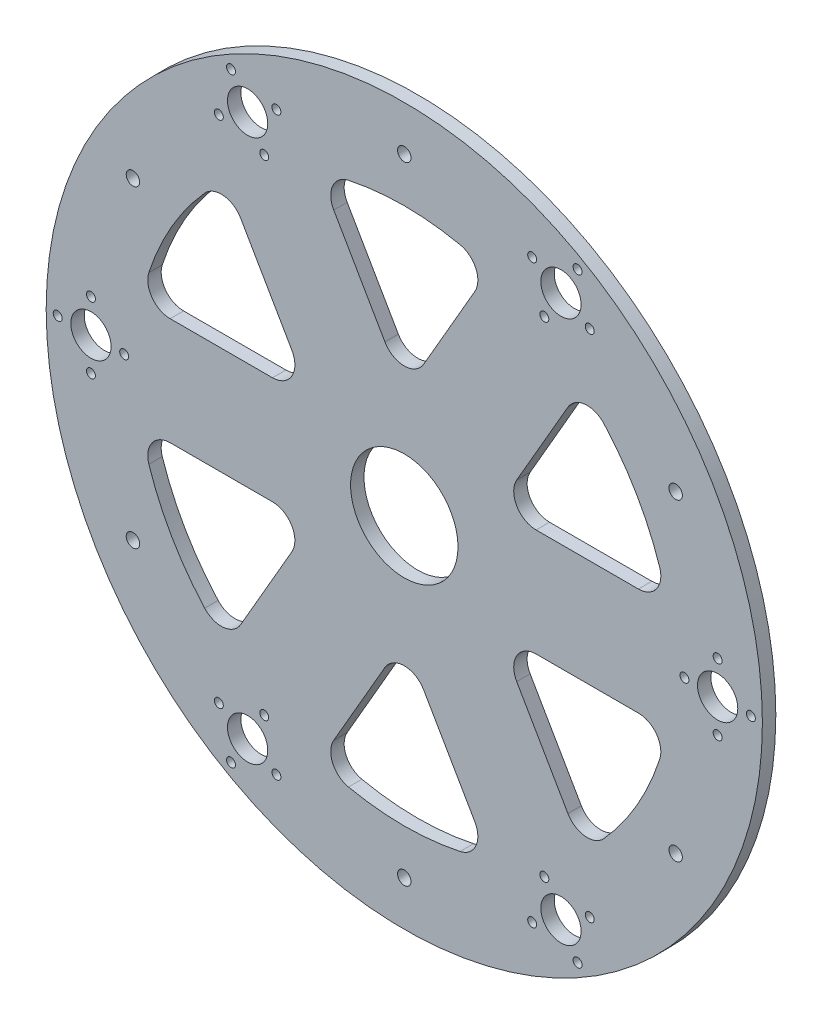
SolidWorks part; units mm, degrees
ref_plane "Front Plane" through (0, 0, 0) normal (0, 0, 1) x (1, 0, 0)
ref_plane "Top Plane" through (0, 0, 0) normal (0, 1, 0) x (1, 0, 0)
ref_plane "Right Plane" through (0, 0, 0) normal (1, 0, 0) x (0, 0, -1)
sketch "Sketch1" plane through (0, 0, 0) normal (0, 0, 1) x (1, 0, 0)
  line L0 (-561.3531, -948.2921) -> (24438.6469, 42352.9781) construction
  line L1 (-540.4731, -960.1269) -> (24459.5269, 42341.1433) construction
  line L2 (460.2716, -773.2137) -> (-24539.7284, 42528.0564) construction
  line L3 (439.0754, -784.5009) -> (-24560.9246, 42516.7693) construction
  line L4 (898.9248, 12) -> (-49101.0752, 12) construction
  line L5 (900.72, -12) -> (-49099.28, -12) construction
  line L18 (-36.5457, 39.299) -> (-25.1147, 19.5)
  line L19 (-29.4449, 12) -> (-52.3068, 12)
  line L20 (15.7611, 51.299) -> (4.3301, 31.5)
  line L21 (-4.3301, 31.5) -> (-15.7611, 51.299)
  line L22 (36.5457, 39.299) -> (25.1147, 19.5)
  line L23 (29.4449, 12) -> (52.3068, 12)
  line L24 (52.3068, -12) -> (29.4449, -12)
  line L25 (25.1147, -19.5) -> (36.5457, -39.299)
  line L26 (15.7611, -51.299) -> (4.3301, -31.5)
  line L27 (-4.3301, -31.5) -> (-15.7611, -51.299)
  line L28 (-36.5457, -39.299) -> (-25.1147, -19.5)
  line L29 (-29.4449, -12) -> (-52.3068, -12)
  circle A0 centre (0, 0) radius 70 construction
  circle A1 centre (70, 0) radius 4.5
  circle A2 centre (70, 0) radius 7.425 construction
  circle A3 centre (77.425, 0) radius 1
  circle A4 centre (70, 7.425) radius 1
  circle A5 centre (62.575, 0) radius 1
  circle A6 centre (70, -7.425) radius 1
  circle A8 centre (35, -60.6218) radius 4.5
  circle A9 centre (41.4302, -56.9093) radius 1
  circle A10 centre (38.7125, -67.052) radius 1
  circle A11 centre (28.5698, -64.3343) radius 1
  circle A12 centre (31.2875, -54.1915) radius 1
  circle A13 centre (35, -60.6218) radius 7.425 construction
  circle A15 centre (-35, -60.6218) radius 4.5
  circle A16 centre (-28.5698, -64.3343) radius 1
  circle A17 centre (-38.7125, -67.052) radius 1
  circle A18 centre (-41.4302, -56.9093) radius 1
  circle A19 centre (-31.2875, -54.1915) radius 1
  circle A20 centre (-35, -60.6218) radius 7.425 construction
  circle A22 centre (-70, 0) radius 4.5
  circle A23 centre (-70, -7.425) radius 1
  circle A24 centre (-77.425, 0) radius 1
  circle A25 centre (-70, 7.425) radius 1
  circle A26 centre (-62.575, 0) radius 1
  circle A27 centre (-70, 0) radius 7.425 construction
  circle A29 centre (-35, 60.6218) radius 4.5
  circle A30 centre (-41.4302, 56.9093) radius 1
  circle A31 centre (-38.7125, 67.052) radius 1
  circle A32 centre (-28.5698, 64.3343) radius 1
  circle A33 centre (-31.2875, 54.1915) radius 1
  circle A34 centre (-35, 60.6218) radius 7.425 construction
  circle A36 centre (35, 60.6218) radius 4.5
  circle A37 centre (28.5698, 64.3343) radius 1
  circle A38 centre (38.7125, 67.052) radius 1
  circle A39 centre (41.4302, 56.9093) radius 1
  circle A40 centre (31.2875, 54.1915) radius 1
  circle A41 centre (35, 60.6218) radius 7.425 construction
  circle A44 centre (0, 0) radius 70 construction
  arc A45 (-57.0619, -18.5455) -> (-44.5918, -40.1444) centre (0, 0) ccw
  circle A46 centre (0, 0) radius 12
  arc A47 (-44.5918, 40.1444) -> (-57.0619, 18.5455) centre (0, 0) ccw
  arc A48 (12.4701, 58.6898) -> (-12.4701, 58.6898) centre (0, 0) ccw
  arc A49 (57.0619, 18.5455) -> (44.5918, 40.1444) centre (0, 0) ccw
  arc A50 (44.5918, -40.1444) -> (57.0619, -18.5455) centre (0, 0) ccw
  arc A51 (-12.4701, -58.6898) -> (12.4701, -58.6898) centre (0, 0) ccw
  arc A52 (-55.7221, -57.4025) -> (29.1551, -74.4982) centre (0, 0) ccw
  arc A53 (29.1551, -74.4982) -> (79.0949, 12) centre (0, 0) ccw
  arc A55 (-29.1551, 74.4982) -> (-55.7221, -57.4025) centre (0, 0) ccw
  arc A56 (79.0949, 12) -> (-29.1551, 74.4982) centre (0, 0) ccw
  circle A57 centre (0, 70) radius 1.5
  circle A58 centre (60.6218, 35) radius 1.5
  circle A59 centre (60.6218, -35) radius 1.5
  circle A60 centre (0, -70) radius 1.5
  circle A61 centre (-60.6218, -35) radius 1.5
  circle A62 centre (-60.6218, 35) radius 1.5
  arc A63 (-25.1147, -19.5) -> (-29.4449, -12) centre (-29.4449, -17) ccw
  arc A64 (-52.3068, -12) -> (-57.0619, -18.5455) centre (-52.3068, -17) ccw
  arc A65 (-44.5918, -40.1444) -> (-36.5457, -39.299) centre (-40.8758, -36.799) ccw
  arc A66 (4.3301, -31.5) -> (-4.3301, -31.5) centre (0, -34) ccw
  arc A67 (-15.7611, -51.299) -> (-12.4701, -58.6898) centre (-11.431, -53.799) ccw
  arc A68 (12.4701, -58.6898) -> (15.7611, -51.299) centre (11.431, -53.799) ccw
  arc A69 (29.4449, -12) -> (25.1147, -19.5) centre (29.4449, -17) ccw
  arc A70 (36.5457, -39.299) -> (44.5918, -40.1444) centre (40.8758, -36.799) ccw
  arc A71 (57.0619, -18.5455) -> (52.3068, -12) centre (52.3068, -17) ccw
  arc A72 (25.1147, 19.5) -> (29.4449, 12) centre (29.4449, 17) ccw
  arc A73 (52.3068, 12) -> (57.0619, 18.5455) centre (52.3068, 17) ccw
  arc A74 (44.5918, 40.1444) -> (36.5457, 39.299) centre (40.8758, 36.799) ccw
  arc A75 (4.3301, 31.5) -> (-4.3301, 31.5) centre (0, 34) cw
  arc A76 (15.7611, 51.299) -> (12.4701, 58.6898) centre (11.431, 53.799) ccw
  arc A77 (-12.4701, 58.6898) -> (-15.7611, 51.299) centre (-11.431, 53.799) ccw
  arc A78 (-57.0619, 18.5455) -> (-52.3068, 12) centre (-52.3068, 17) ccw
  arc A79 (-29.4449, 12) -> (-25.1147, 19.5) centre (-29.4449, 17) ccw
  arc A80 (-36.5457, 39.299) -> (-44.5918, 40.1444) centre (-40.8758, 36.799) ccw
  point P77 (0, 0)
  point P152 (0, 0)
  point P153 (-20.7846, -12)
  point P156 (-58.7878, -12)
  point P159 (-39.7862, -44.9117)
  point P162 (0, -24)
  point P165 (-19.0016, -56.9117)
  point P168 (19.0016, -56.9117)
  point P171 (20.7846, -12)
  point P174 (39.7862, -44.9117)
  point P177 (58.7878, -12)
  point P180 (20.7846, 12)
  point P183 (58.7878, 12)
  point P186 (39.7862, 44.9117)
  point P189 (0, 24)
  point P192 (19.0016, 56.9117)
  point P195 (-19.0016, 56.9117)
  point P198 (-58.7878, 12)
  point P201 (-20.7846, 12)
  point P204 (-39.7862, 44.9117)
  point P207 (79.0949, 12)
  point P210 (79.0949, -12)
  point P219 (-29.1551, -74.4982)
  point P222 (-49.9397, -62.4982)
  point P225 (-79.0949, -12)
  point P228 (-79.0949, 12)
  point P233 (49.9397, 62.4982)
  point P236 (29.1551, 74.4982)
  point P239 (-29.1551, 74.4982)
  dimension "D1" = 6
  dimension "D2" = 5
  dimension "D3" = 9
  dimension "D4" = 14.85
  dimension "D5" = 2
  dimension "D6" = 2
  dimension "D7" = 2
  dimension "D8" = 2
  dimension "D10" = 80
  dimension "D11" = 140
  dimension "D12" = 60
  dimension "D14" = 3
  dimension "D17" = 140
  dimension "D18" = 22.8619
  dimension "D20" = 70
  dimension "D19" = 22.8619
  dimension "D21" = 70
  dimension "D13" = 6
extrude "Boss-Extrude1" add sketch "Sketch1" along normal blind 3
